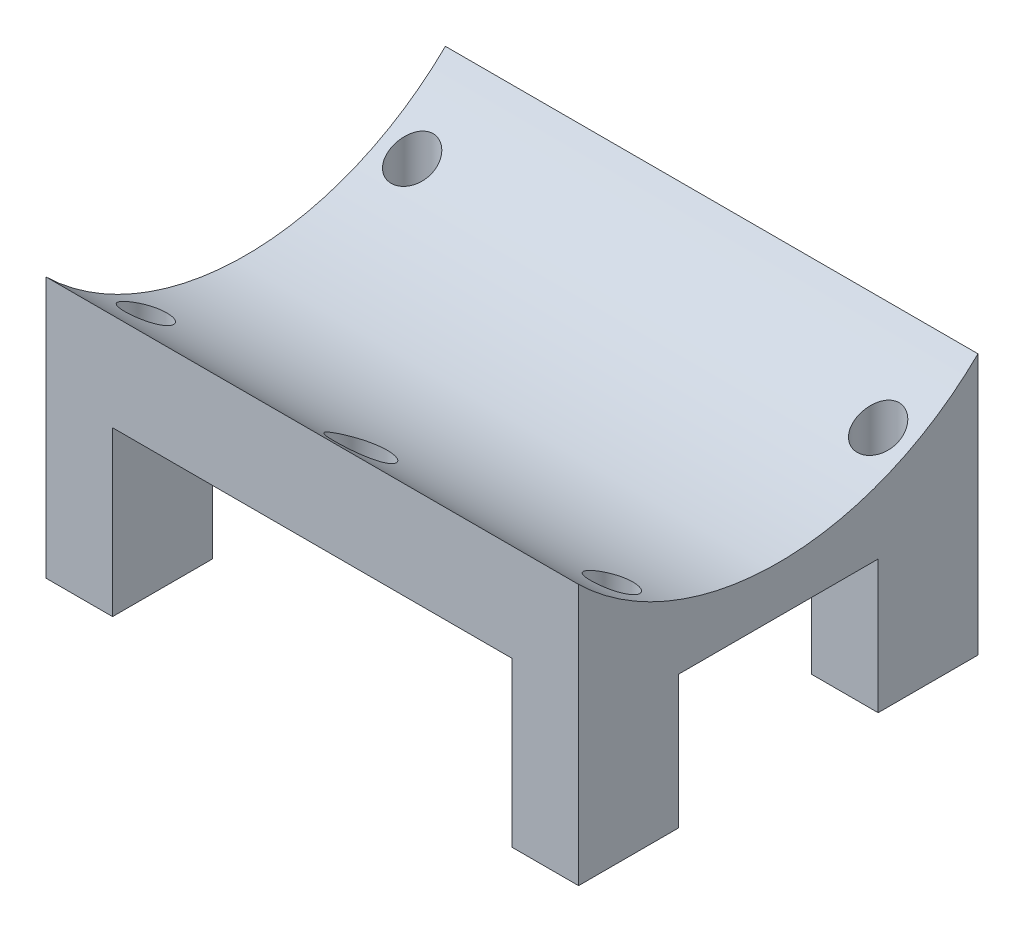
SolidWorks part; units mm, degrees
ref_plane "Front Plane" through (0, 0, 0) normal (0, 0, 1) x (1, 0, 0)
ref_plane "Top Plane" through (0, 0, 0) normal (0, 1, 0) x (1, 0, 0)
ref_plane "Right Plane" through (0, 0, 0) normal (1, 0, 0) x (0, 0, -1)
sketch "Sketch1" plane through (0, 0, 0) normal (1, 0, 0) x (0, 0, -1)
  line L2 (-38.1, 37.0766) -> (-38.1, -12.7)
  line L3 (-38.1, -12.7) -> (38.1, -12.7)
  line L4 (38.1, 37.0766) -> (38.1, -12.7)
  arc A0 (-38.1, 37.0766) -> (38.1, 37.0766) centre (0, 76.2) ccw
  point P0 (0, 0)
  dimension "D3" = 88.9
extrude "Boss-Extrude1" add sketch "Sketch1" along normal blind 101.6
sketch "Sketch2" plane through (0, -12.7, 0) normal (0, -1, 0) x (-1, 0, 0)
  line L0 (-101.6, -38.1) -> (0, -38.1) construction
  line L1 (0, -38.1) -> (0, 38.1) construction
  line L2 (-101.6, -38.1) -> (-101.6, 38.1) construction
  circle A0 centre (-6.35, -25.4) radius 2
  circle A1 centre (-6.35, 25.4) radius 2
  circle A2 centre (-95.25, -25.4) radius 2
  circle A3 centre (-95.25, 25.4) radius 2
  dimension "D1" = 12.7
  dimension "D2" = 4
  dimension "D3" = 6.35
  dimension "D4" = 6.35
  dimension "D5" = 50.8
extrude "Cut-Extrude1" cut sketch "Sketch2" against normal through all
sketch "Sketch3" plane through (0, 0, -38.1) normal (0, 0, -1) x (-1, 0, 0)
  line L0 (-101.6, -12.7) -> (0, -12.7) construction
  line L1 (-88.9, -43.913) -> (-12.7, -43.913)
  line L2 (-88.9, -43.913) -> (-88.9, 18.513)
  line L3 (-88.9, 18.513) -> (-12.7, 18.513)
  line L4 (-12.7, -43.913) -> (-12.7, 18.513)
  line L5 (-88.9, -43.913) -> (-12.7, 18.513) construction
  line L6 (-88.9, 18.513) -> (-12.7, -43.913) construction
  point P0 (-50.8, -12.7)
  dimension "D1" = 76.2
extrude "Cut-Extrude2" cut sketch "Sketch3" against normal through all
sketch "Sketch4" plane through (101.6, 0, 0) normal (1, 0, 0) x (0, 0, -1)
  line L0 (-38.1, 37.0766) -> (-38.1, 33.6029)
  line L2 (38.1, 37.0766) -> (38.1, 33.6029)
  arc A0 (-38.1, 37.0766) -> (38.1, 37.0766) centre (0, 76.2) ccw
  arc A1 (-38.1, 33.6029) -> (38.1, 33.6029) centre (0, 76.2) ccw
  circle A3 centre (0, 76.2) radius 57.15 construction
  circle A4 centre (0, 76.2) radius 54.61 construction
  point P4 (0, 102.87)
  point P7 (57.15, 48.26)
  dimension "D1" = 2.54
extrude "Boss-Extrude2" add sketch "Sketch4" against normal blind 76.2
ref_plane "Plane1" through (0, 17.78, 0) normal (0, -1, 0) x (-1, 0, 0)
sketch "Sketch5" plane through (0, 17.78, 0) normal (0, -1, 0) x (-1, 0, 0)
  line L0 (0, -38.1) -> (0, 38.1) construction
  circle A0 centre (-95.25, 25.4) radius 4
  circle A1 centre (-6.35, 25.4) radius 4
  circle A2 centre (-6.35, -25.4) radius 4
  circle A3 centre (-95.25, -25.4) radius 4
  dimension "D1" = 6.35
extrude "Cut-Extrude3" cut sketch "Sketch5" along normal blind 27.94 and the other way blind 19.05
sketch "Sketch6" plane through (101.6, 0, 0) normal (1, 0, 0) x (0, 0, -1)
  line L0 (-38.1, -12.7) -> (38.1, -12.7) construction
  line L1 (-19.05, 12.7) -> (19.05, 12.7)
  line L2 (-19.05, 12.7) -> (-19.05, -38.1)
  line L3 (-19.05, -38.1) -> (19.05, -38.1)
  line L4 (19.05, 12.7) -> (19.05, -38.1)
  line L5 (-19.05, 12.7) -> (19.05, -38.1) construction
  line L6 (-19.05, -38.1) -> (19.05, 12.7) construction
  point P0 (0, -12.7)
  dimension "D1" = 38.1
  dimension "D2" = 25.4
extrude "Cut-Extrude4" cut sketch "Sketch6" against normal through all
ref_plane "Plane2" through (0, 38.1, 0) normal (0, -1, 0) x (-1, 0, 0)
sketch "Sketch9" plane through (0, 38.1, 0) normal (0, -1, 0) x (-1, 0, 0)
  circle A0 centre (-51.4751, -29.5223) radius 5
extrude "Cut-Extrude6" cut sketch "Sketch9" along normal blind 15.24
sketch "Sketch10" plane through (0, 17.78, 0) normal (0, -1, 0) x (-1, 0, 0)
  circle A0 centre (-51.4751, -29.5223) radius 2.5
extrude "Cut-Extrude7" cut sketch "Sketch10" against normal through all
